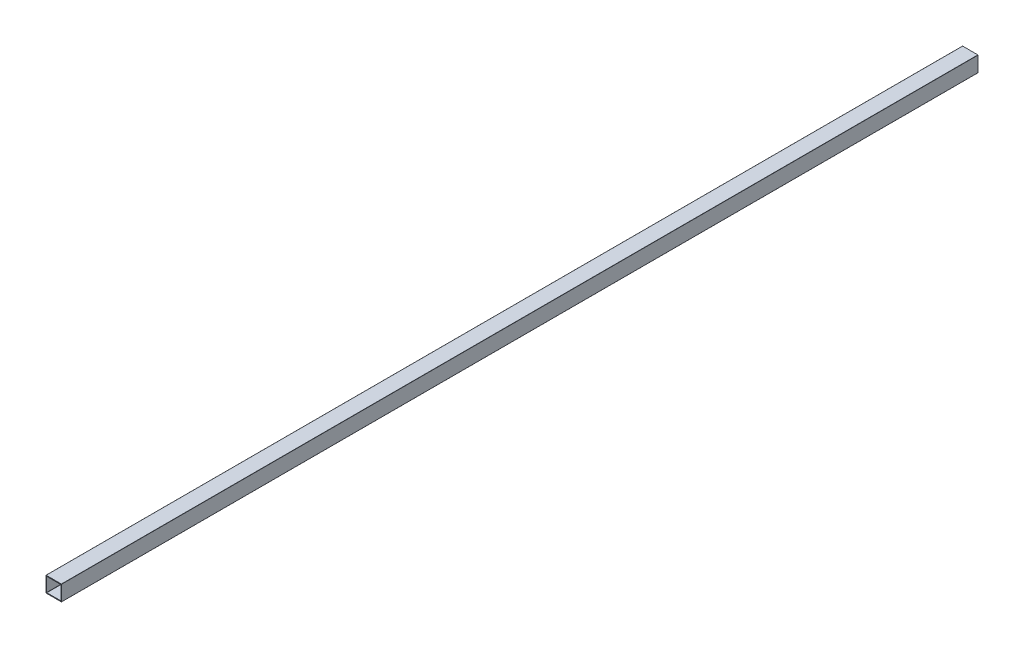
SolidWorks part; units mm, degrees
material "AISI 1035 Acero (SS)"
ref_plane "Alzado" through (0, 0, 0) normal (0, 0, 1) x (1, 0, 0)
ref_plane "Planta" through (0, 0, 0) normal (0, 1, 0) x (1, 0, 0)
ref_plane "Vista lateral" through (0, 0, 0) normal (1, 0, 0) x (0, 0, -1)
sketch "Croquis1" plane through (0, 0, 0) normal (0, 0, 1) x (1, 0, 0)
  line L0 (-46.25, -46.25) -> (-46.25, 46.25)
  line L1 (-50.8, -50.8) -> (50.8, -50.8)
  line L2 (-50.8, -50.8) -> (-50.8, 50.8)
  line L3 (-50.8, 50.8) -> (50.8, 50.8)
  line L4 (50.8, -50.8) -> (50.8, 50.8)
  line L5 (-50.8, -50.8) -> (50.8, 50.8) construction
  line L6 (-50.8, 50.8) -> (50.8, -50.8) construction
  line L7 (-46.25, 46.25) -> (46.25, 46.25)
  line L8 (46.25, -46.25) -> (46.25, 46.25)
  line L9 (-46.25, -46.25) -> (46.25, -46.25)
  point P0 (0, 0)
  dimension "D2" = 101.6
  dimension "D3" = 4.55
extrude "Saliente-Extruir1" add sketch "Croquis1" against normal blind 6000
fillet "Redondeo1" radius 1 8 edges at (-46.25, 46.25, -3000) (46.25, 46.25, -3000) (46.25, -46.25, -3000) (-50.8, -50.8, -3000) (-50.8, 50.8, -3000) (-46.25, -46.25, -3000) (50.8, -50.8, -3000) (50.8, 50.8, -3000)
